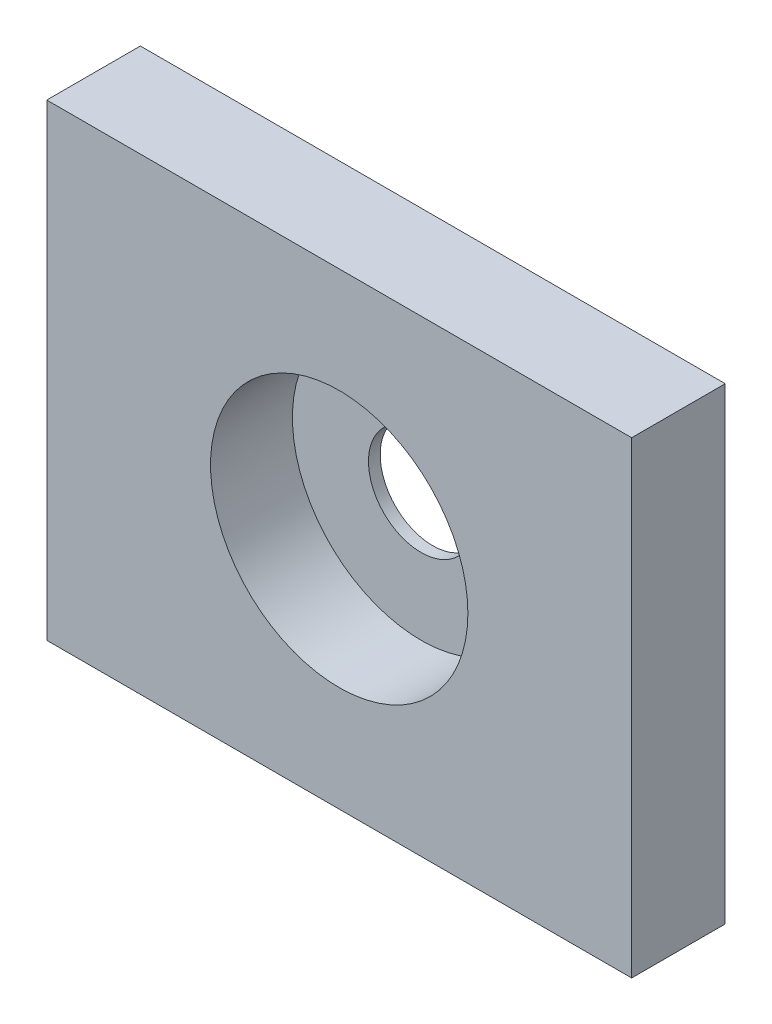
SolidWorks part; units mm, degrees
ref_plane "Front" through (0, 0, 0) normal (0, 0, 1) x (1, 0, 0)
ref_plane "Top" through (0, 0, 0) normal (0, 1, 0) x (1, 0, 0)
ref_plane "Right" through (0, 0, 0) normal (1, 0, 0) x (0, 0, -1)
sketch "Esquisse1" plane through (0, 0, 0) normal (0, 0, 1) x (1, 0, 0)
  line L0 (25, 0) -> (25, 20) construction
  line L1 (0, 0) -> (50, 0)
  line L2 (0, 0) -> (0, 40)
  line L3 (0, 40) -> (50, 40)
  line L4 (50, 0) -> (50, 40)
  circle A0 centre (25, 20) radius 4.5
  dimension "D1" = 20
  dimension "D2" = 9
  dimension "D3" = 50
  dimension "D4" = 40
extrude "Boss.-Extru.1" add sketch "Esquisse1" along normal blind 8
sketch "Esquisse2" plane through (0, 0, 8) normal (0, 0, 1) x (1, 0, 0)
  circle A0 centre (25, 20) radius 11
  dimension "D1" = 22
extrude "Enlèv. mat.-Extru.1" cut sketch "Esquisse2" against normal blind 7
